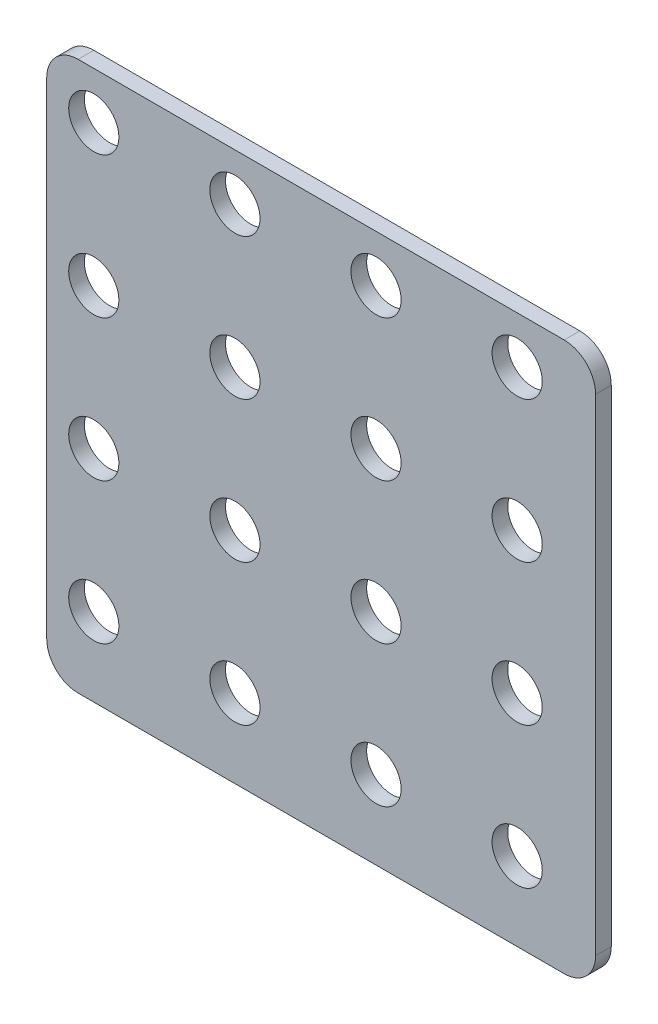
SolidWorks part; units mm, degrees
ref_plane "Front Plane" through (0, 0, 0) normal (0, 0, 1) x (1, 0, 0)
ref_plane "Top Plane" through (0, 0, 0) normal (0, 1, 0) x (1, 0, 0)
ref_plane "Right Plane" through (0, 0, 0) normal (1, 0, 0) x (0, 0, -1)
sketch "Sketch1" plane through (0, 0, 0) normal (0, 0, 1) x (1, 0, 0)
  line L1 (0, 0) -> (35, 0)
  line L2 (0, 0) -> (0, 35)
  line L3 (0, 35) -> (35, 35)
  line L4 (35, 0) -> (35, 35)
  dimension "D1" = 35
  dimension "D2" = 35
extrude "Boss-Extrude1" add sketch "Sketch1" along normal blind 1
sketch "Sketch2" plane through (0, 0, 1) normal (0, 0, 1) x (1, 0, 0)
  line L0 (0, 35) -> (0, 0) construction
  line L1 (35, 35) -> (0, 35) construction
  circle A0 centre (3, 32) radius 1.6
  dimension "D1" = 3.2
  dimension "D2" = 3
  dimension "D3" = 3
extrude "Cut-Extrude1" cut sketch "Sketch2" against normal through all both and the other way through all
pattern_linear "LPattern1" count 4 spacing 9 along (1, 0, 0) count 4 spacing 9 along (0, -1, 0) of "Cut-Extrude1"
fillet "Fillet1" radius 2 4 edges at (0, 0, 0.5) (35, 0, 0.5) (35, 35, 0.5) (0, 35, 0.5)
